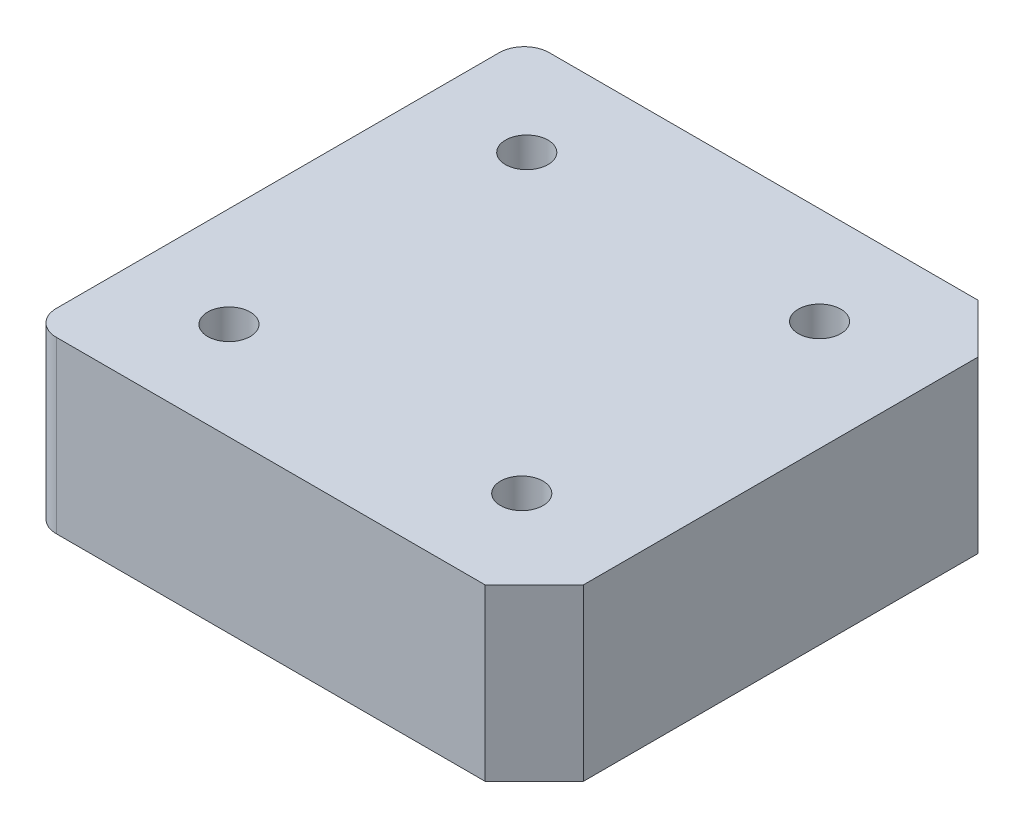
SolidWorks part; units mm, degrees
material "ABS"
ref_plane "Front Plane" through (0, 0, 0) normal (0, 0, 1) x (1, 0, 0)
ref_plane "Top Plane" through (0, 0, 0) normal (0, 1, 0) x (1, 0, 0)
ref_plane "Right Plane" through (0, 0, 0) normal (1, 0, 0) x (0, 0, -1)
sketch "Sketch1" plane through (0, 0, 0) normal (0, 1, 0) x (1, 0, 0)
  line L1 (-35.8327, 23.3971) -> (15.2213, 23.3971)
  line L2 (-35.8327, 23.3971) -> (-35.8327, -26.6409)
  line L3 (-35.8327, -26.6409) -> (15.2213, -26.6409)
  line L4 (15.2213, 23.3971) -> (15.2213, -26.6409)
  dimension "D1" = 50.038
  dimension "D2" = 51.054
extrude "Boss-Extrude1" add sketch "Sketch1" along normal blind 17.272
chamfer "Chamfer1" distance 5 angle 45 2 edges at (15.2213, 8.636, -23.3971) (15.2213, 8.636, 26.6409)
fillet "Fillet1" radius 2.54 2 edges at (-35.8327, 8.636, 26.6409) (-35.8327, 8.636, -23.3971)
sketch "Sketch2" plane through (0, 17.272, 0) normal (0, 1, 0) x (1, 0, 0)
  line L0 (15.2213, -21.6409) -> (15.2213, 18.3971) construction
  line L1 (10.2213, 23.3971) -> (-33.2927, 23.3971) construction
  line L2 (-33.2927, -26.6409) -> (10.2213, -26.6409) construction
  circle A0 centre (-25.6727, 13.4911) radius 2.159
  circle A1 centre (4.0453, 13.4911) radius 2.159
  circle A2 centre (4.0453, -16.7349) radius 2.159
  circle A3 centre (-25.6727, -16.7349) radius 2.159
  point P8 (0, 0)
  point P11 (0, 0)
  point P14 (0, 0)
  point P17 (0, 0)
  point P18 (0, 0)
  dimension "D4" = 4.318
  dimension "D1" = 11.176
  dimension "D2" = 9.906
  dimension "D3" = 29.718
  dimension "D5" = 9.906
extrude "Cut-Extrude1" cut sketch "Sketch2" against normal through all
